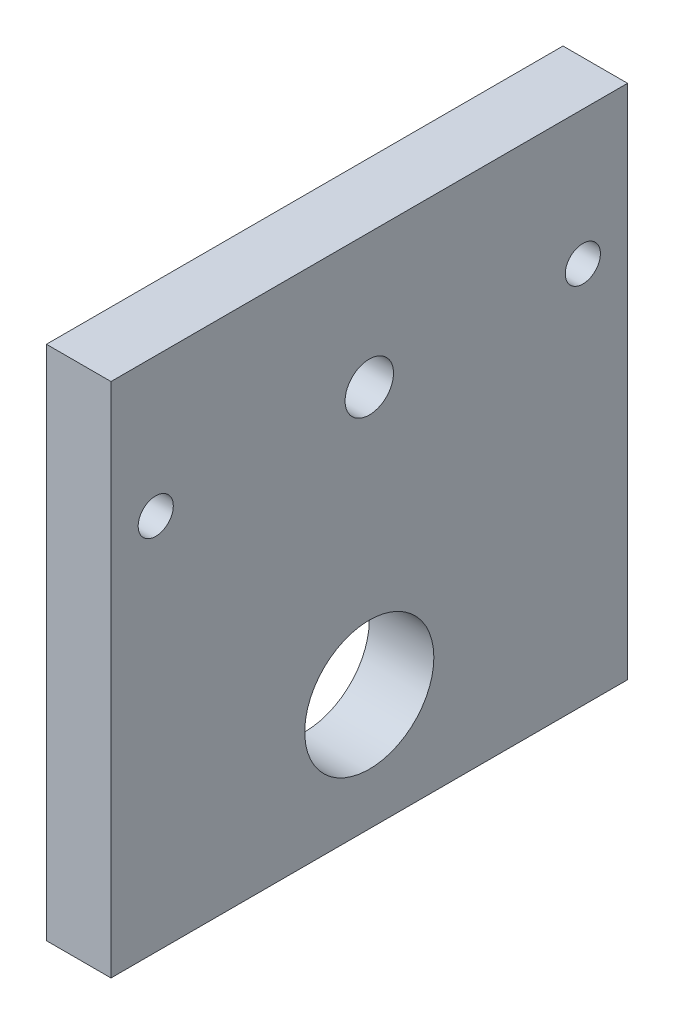
SolidWorks part; units mm, degrees
ref_plane "Front Plane" through (0, 0, 0) normal (0, 0, 1) x (1, 0, 0)
ref_plane "Top Plane" through (0, 0, 0) normal (0, 1, 0) x (1, 0, 0)
ref_plane "Right Plane" through (0, 0, 0) normal (1, 0, 0) x (0, 0, -1)
sketch "Sketch1" plane through (0, 0, 0) normal (1, 0, 0) x (0, 0, -1)
  line L1 (-25.4, -25.4) -> (25.4, -25.4)
  line L2 (-25.4, -25.4) -> (-25.4, 25.4)
  line L3 (-25.4, 25.4) -> (25.4, 25.4)
  line L4 (25.4, -25.4) -> (25.4, 25.4)
  line L5 (-25.4, -25.4) -> (25.4, 25.4) construction
  line L6 (-25.4, 25.4) -> (25.4, -25.4) construction
  point P0 (0, 0)
  dimension "D1" = 50.8
  dimension "D2" = 50.8
extrude "Boss-Extrude1" add sketch "Sketch1" along normal blind 6.35
hole_wizard "1/2 (0.5) Diameter Hole1" positions "Sketch9" profile "Sketch8" hole size "1/2" standard "ANSI Inch"
sketch "Sketch9" plane through (6.35, 0, 0) normal (1, 0, 0) x (0, 0, -1)
  line L0 (-25.4, -25.4) -> (25.4, -25.4) construction
  point P0 (0, -13.97)
  dimension "D1" = 11.43
sketch "Sketch8" plane through (6.35, -13.97, 0) normal (0, 1, 0) x (0, 0, -1)
  line L0 (0, 0) -> (0, 73.9195)
  line L1 (0, 73.9195) -> (6.35, 70.104)
  line L2 (6.35, 70.104) -> (6.35, 0)
  line L5 (6.35, 0) -> (0, 0)
  line L10 (0, 73.9195) -> (-6.35, 70.104) construction
  line L11 (0, -6.35) -> (0, 107.95) construction
  dimension "Hole Dia." = 12.7
  dimension "Hole Depth" = 70.104
  dimension "Drill Angle" = 118
hole_wizard "3/16 (0.1875) Diameter Hole1" positions "Sketch3" profile "Sketch2" hole size "3/16" standard "ANSI Inch"
sketch "Sketch3" plane through (6.35, 0, 0) normal (1, 0, 0) x (0, 0, -1)
  circle A0 centre (0, -13.97) radius 6.35 construction
  point P0 (0, 12.2301)
  dimension "D1" = 26.2001
  dimension "D2" = 0
sketch "Sketch2" plane through (6.35, 12.2301, 0) normal (0, 1, 0) x (0, 0, -1)
  line L0 (0, 0) -> (0, 71.5348)
  line L1 (0, 71.5348) -> (2.3812, 70.104)
  line L2 (2.3812, 70.104) -> (2.3812, 0)
  line L5 (2.3812, 0) -> (0, 0)
  line L10 (0, 71.5348) -> (-2.3813, 70.104) construction
  line L11 (0, -6.35) -> (0, 107.95) construction
  dimension "Hole Dia." = 4.7625
  dimension "Hole Depth" = 70.104
  dimension "Drill Angle" = 118
hole_wizard "#29 (0.136) Diameter Hole1" positions "Sketch5" profile "Sketch4" hole size "#29" standard "ANSI Inch"
sketch "Sketch5" plane through (6.35, 0, 0) normal (1, 0, 0) x (0, 0, -1)
  circle A0 centre (0, 12.2301) radius 2.3812 construction
  point P0 (21, 12.2301)
  point P2 (-21, 11.7415)
  dimension "D1" = 0.4886
  dimension "D2" = 0
  dimension "D3" = 21
  dimension "D4" = 42
sketch "Sketch4" plane through (6.35, 12.2301, -21) normal (0, 1, 0) x (0, 0, -1)
  line L0 (0, 0) -> (0, 71.1418)
  line L1 (0, 71.1418) -> (1.7272, 70.104)
  line L2 (1.7272, 70.104) -> (1.7272, 0)
  line L5 (1.7272, 0) -> (0, 0)
  line L10 (0, 71.1418) -> (-1.7272, 70.104) construction
  line L11 (0, -6.35) -> (0, 107.95) construction
  dimension "Hole Dia." = 3.4544
  dimension "Hole Depth" = 70.104
  dimension "Drill Angle" = 118
hole_wizard "#10-32 Tapped Hole1" positions "Sketch11" profile "Sketch10" tap size "#10-32" standard "ANSI Inch"
sketch "Sketch11" plane through (-0.6693, 7.9801, -25.4) normal (0, 0, -1) x (-1, 0, 0)
  line L0 (-7.0193, 17.4199) -> (-0.6693, 17.4199) construction
  line L2 (-7.0193, -33.3801) -> (-0.6693, -33.3801) construction
  line L3 (-7.0193, 17.4199) -> (-0.6693, 17.4199) construction
  point P0 (-3.8443, -27.0301)
  point P2 (-3.8443, 11.0699)
  point P6 (-3.8443, 17.4199)
  dimension "D1" = 0
  dimension "D2" = 0
  dimension "D3" = 6.35
  dimension "D4" = 6.35
sketch "Sketch10" plane through (3.175, -19.05, -25.4) normal (1, 0, 0) x (0, 1, 0)
  line L0 (0, 0) -> (0, 13.1513)
  line L1 (0, 13.1513) -> (2.0193, 11.938)
  line L2 (2.0193, 11.938) -> (2.0193, 0)
  line L5 (2.0193, 0) -> (0, 0)
  line L10 (0, 13.1513) -> (-2.0193, 11.938) construction
  line L11 (0, -6.35) -> (0, 107.95) construction
  dimension "Tap Drill Dia." = 4.0386
  dimension "Tap Drill Depth" = 11.938
  dimension "Drill Angle" = 118
cosmetic thread "Hole Thread1"
cosmetic thread "Hole Thread2"
